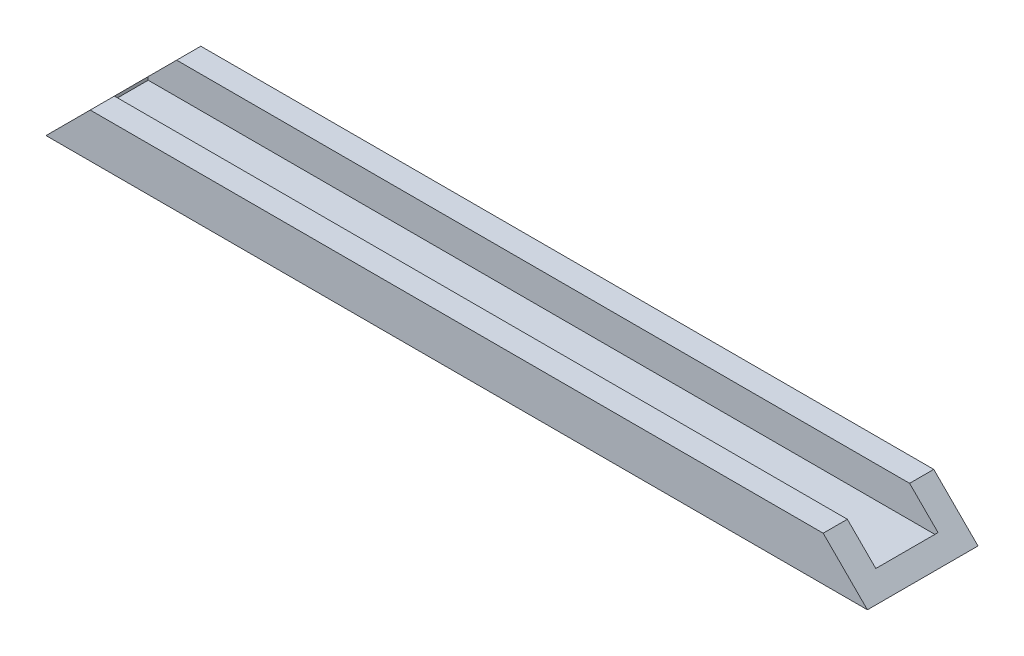
SolidWorks part; units mm, degrees
material "Copper"
ref_plane "Front Plane" through (0, 0, 0) normal (0, 0, 1) x (1, 0, 0)
ref_plane "Top Plane" through (0, 0, 0) normal (0, 1, 0) x (1, 0, 0)
ref_plane "Right Plane" through (0, 0, 0) normal (1, 0, 0) x (0, 0, -1)
sketch "Sketch1" plane through (0, 0, 0) normal (0, 1, 0) x (1, 0, 0)
  line L1 (0, 0) -> (165.1, 0)
  line L2 (0, 0) -> (0, 22.225)
  line L3 (0, 22.225) -> (165.1, 22.225)
  line L4 (165.1, 0) -> (165.1, 22.225)
  dimension "D1" = 165.1
  dimension "D2" = 22.225
extrude "Base Extrude" add sketch "Sketch1" along normal blind 8.89
sketch "Sketch3" plane through (0, 8.89, 0) normal (0, 1, 0) x (1, 0, 0)
  line L1 (3.175, 17.3673) -> (161.925, 17.3672)
  line L2 (3.175, 17.3673) -> (3.175, 4.8577)
  line L3 (3.175, 4.8577) -> (161.925, 4.8577)
  line L4 (161.925, 17.3672) -> (161.925, 4.8577)
  line L5 (0, 22.225) -> (0, 0) construction
  line L6 (165.1, 0) -> (165.1, 22.225) construction
  line L8 (3.175, 11.1125) -> (161.925, 11.1125) construction
  line L9 (165.1, 11.1125) -> (0, 11.1125) construction
  dimension "D1" = 12.5095
  dimension "D2" = 158.75
  dimension "D3" = 3.175
extrude "Piece Cut" cut sketch "Sketch3" against normal blind 6.35
sketch "Sketch4" plane through (0, 0, -22.225) normal (0, 0, -1) x (-1, 0, 0)
  line L0 (0, 0) -> (-8.89, 8.89)
  line L1 (-165.1, 8.89) -> (0, 8.89) construction
  line L2 (0, 0) -> (0, 8.89)
  line L3 (0, 8.89) -> (-8.89, 8.89)
  line L4 (-82.55, 0) -> (-82.55, 8.89) construction
  line L5 (-165.1, 0) -> (0, 0) construction
  line L6 (-165.1, 8.89) -> (-156.21, 8.89)
  line L7 (-165.1, 0) -> (-165.1, 8.89)
  line L8 (-165.1, 0) -> (-156.21, 8.89)
  dimension "D1" = 45
extrude "Corner Cut" cut sketch "Sketch4" against normal through all
